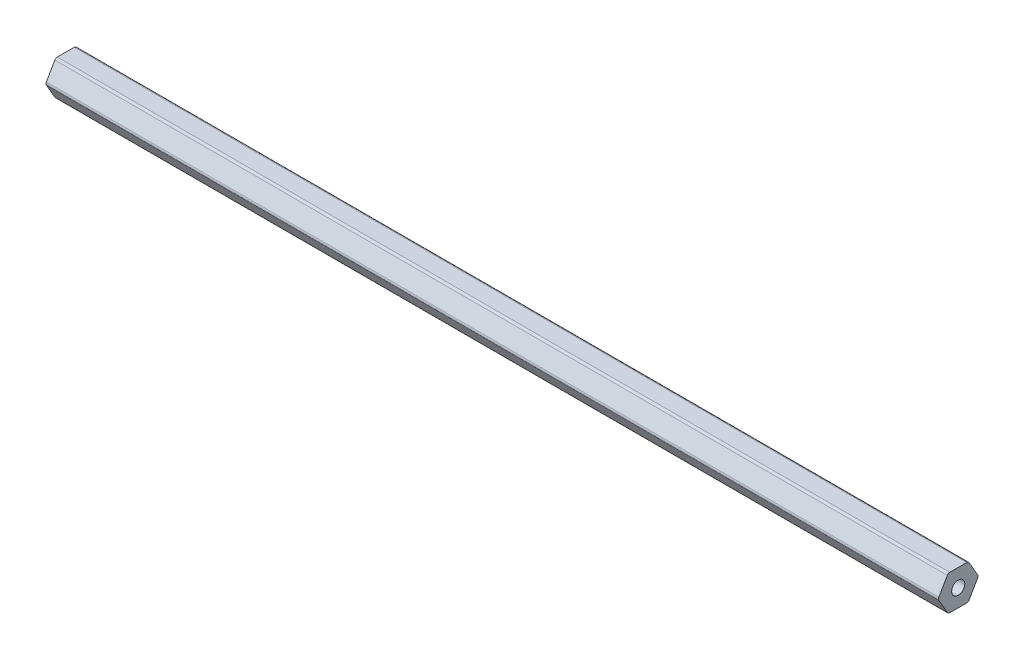
SolidWorks part; units mm, degrees
material "7075-T6 (SN)"
ref_plane "Front Plane" through (0, 0, 0) normal (0, 0, 1) x (1, 0, 0)
ref_plane "Top Plane" through (0, 0, 0) normal (0, 1, 0) x (1, 0, 0)
ref_plane "Right Plane" through (0, 0, 0) normal (1, 0, 0) x (0, 0, -1)
sketch "Sketch1" plane through (0, 0, 0) normal (1, 0, 0) x (0, 0, -1)
  line L1 (7.0391, 0.508) -> (3.9595, 5.842)
  line L2 (3.0796, 6.35) -> (-3.0796, 6.35)
  line L3 (-3.9595, 5.842) -> (-7.0391, 0.508)
  line L4 (-7.0391, -0.508) -> (-3.9595, -5.842)
  line L5 (-3.0796, -6.35) -> (3.0796, -6.35)
  line L6 (3.9595, -5.842) -> (7.0391, -0.508)
  circle A0 centre (0, 0) radius 6.35 construction
  arc A1 (3.0796, 6.35) -> (3.9595, 5.842) centre (3.0796, 5.334) cw
  arc A2 (7.0391, 0.508) -> (7.0391, -0.508) centre (6.1592, 0) cw
  arc A3 (3.9595, -5.842) -> (3.0796, -6.35) centre (3.0796, -5.334) cw
  arc A4 (-3.0796, -6.35) -> (-3.9595, -5.842) centre (-3.0796, -5.334) cw
  arc A5 (-7.0391, -0.508) -> (-7.0391, 0.508) centre (-6.1592, 0) cw
  arc A6 (-3.9595, 5.842) -> (-3.0796, 6.35) centre (-3.0796, 5.334) cw
  circle A7 centre (0, 0) radius 2.3813
  point P11 (3.6662, 6.35)
  point P14 (7.3323, 0)
  dimension "D1" = 12.7
  dimension "D3" = 1.016
  dimension "D4" = 4.7625
  dimension "D2" = 6.35
extrude "Boss-Extrude1" add sketch "Sketch1" along normal blind 323.85
